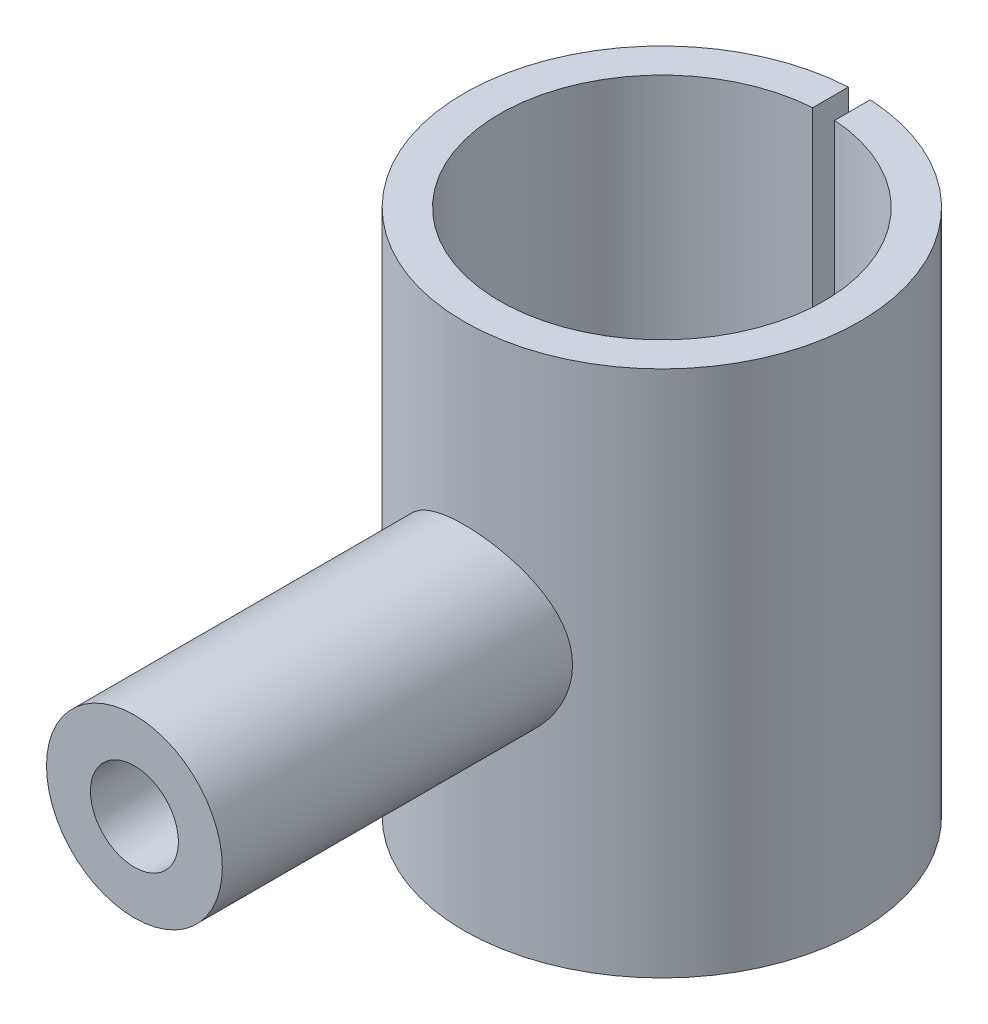
SolidWorks part; units mm, degrees
ref_plane "Front Plane" through (0, 0, 0) normal (0, 0, 1) x (1, 0, 0)
ref_plane "Top Plane" through (0, 0, 0) normal (0, 1, 0) x (1, 0, 0)
ref_plane "Right Plane" through (0, 0, 0) normal (1, 0, 0) x (0, 0, -1)
ref_plane "Plane1" through (0, 0, 31.75) normal (0, 0, 1) x (1, 0, 0)
sketch "Sketch1" plane through (0, 0, 0) normal (0, 1, 0) x (1, 0, 0)
  circle A0 centre (0, 0) radius 23.4315
  circle A1 centre (0, 0) radius 28.575
  dimension "D1" = 46.863
  dimension "D2" = 57.15
extrude "Boss-Extrude1" add sketch "Sketch1" along normal blind 76.2
sketch "Sketch2" plane through (0, 0, 0) normal (0, 0, 1) x (1, 0, 0)
  line L0 (-28.575, 38.1) -> (28.575, 38.1)
  line L1 (-28.575, 76.2) -> (-28.575, 0) construction
  line L2 (28.575, 0) -> (28.575, 76.2) construction
  circle A0 centre (0, 38.1) radius 12.7
  circle A1 centre (0, 38.1) radius 6.35
  dimension "D1" = 12.7
  dimension "D2" = 25.4
extrude "Boss-Extrude2" add sketch "Sketch2" along normal blind 76.2 contours A1 L0 A0 | A1 L0 A0
sketch "Sketch5" plane through (0, 0, 31.75) normal (0, 0, 1) x (1, 0, 0)
  circle A0 centre (0, 38.1) radius 12.7
  dimension "D1" = 25.4
extrude "Boss-Extrude4" add sketch "Sketch5" against normal blind 31.75
sketch "Sketch3" plane through (0, 76.2, 0) normal (0, 1, 0) x (1, 0, 0)
  circle A0 centre (0, 0) radius 23.4315
extrude "Cut-Extrude1" cut sketch "Sketch3" against normal through all
sketch "Sketch6" plane through (0, 76.2, 0) normal (0, 1, 0) x (1, 0, 0)
  line L1 (-1.5875, 6.1533) -> (1.5875, 6.1533)
  line L2 (-1.5875, 6.1533) -> (-1.5875, 40.7097)
  line L3 (-1.5875, 40.7097) -> (1.5875, 40.7097)
  line L4 (1.5875, 6.1533) -> (1.5875, 40.7097)
  line L5 (-1.5875, 6.1533) -> (1.5875, 40.7097) construction
  line L6 (-1.5875, 40.7097) -> (1.5875, 6.1533) construction
  circle A0 centre (0, 0) radius 23.4315 construction
  point P0 (0, 23.4315)
  dimension "D1" = 3.175
extrude "Cut-Extrude2" cut sketch "Sketch6" against normal through all
